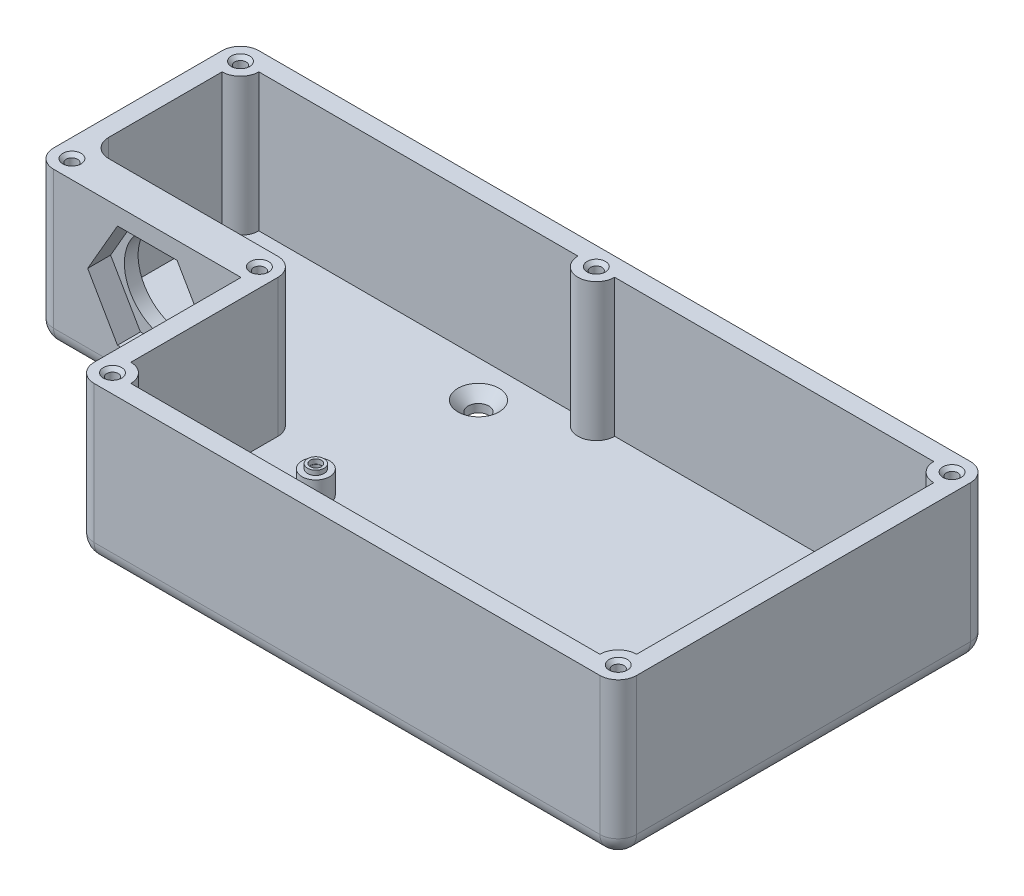
SolidWorks part; units mm, degrees
ref_plane "Alzado" through (0, 0, 0) normal (0, 0, 1) x (1, 0, 0)
ref_plane "Planta" through (0, 0, 0) normal (0, 1, 0) x (1, 0, 0)
ref_plane "Vista lateral" through (0, 0, 0) normal (1, 0, 0) x (0, 0, -1)
sketch "Croquis2" plane through (0, 0, 0) normal (0, 1, 0) x (1, 0, 0)
  line L0 (0, 0) -> (90.17, 0)
  line L1 (90.17, 0) -> (90.3175, 47.7203)
  line L2 (90.3175, 47.7203) -> (0.1588, 47.6975)
  line L3 (0.1588, 47.6975) -> (0, 0)
  circle A0 centre (5.2388, 19.05) radius 2
  circle A1 centre (85.2488, 8.7503) radius 1.5
  circle A2 centre (85.2488, 44.1516) radius 1.5
sketch "Croquis3" plane through (0, 0, 0) normal (0, 1, 0) x (1, 0, 0)
  circle A0 centre (85.2488, 8.7503) radius 1.5 construction
  circle A1 centre (85.2488, 44.1516) radius 1.5 construction
  circle A2 centre (5.2388, 19.05) radius 2 construction
  circle A3 centre (85.2488, 8.7503) radius 1.5 construction
  circle A4 centre (85.2488, 44.1516) radius 1.5 construction
  circle A5 centre (5.2388, 19.05) radius 2 construction
  circle A6 centre (5.2388, 19.05) radius 3
  circle A7 centre (85.2488, 44.1516) radius 2.5
  circle A8 centre (85.2488, 8.7503) radius 2.5
  dimension "D1" = 1
extrude "Saliente-Extruir1" add sketch "Croquis3" along normal blind 5
hole_wizard "Taladro de margen para M21" positions "Croquis6" profile "Croquis8" hole size "M2" standard "Ansi Metric" end condition through all
sketch "Croquis6" plane through (0, 5, 0) normal (0, 1, 0) x (1, 0, 0)
  point P0 (5.2388, 19.05)
  point P3 (85.2488, 44.1516)
  point P6 (85.2488, 8.7503)
sketch "Croquis8" plane through (5.2388, 5, -19.05) normal (1, 0, 0) x (0, 0, 1)
  line L0 (0, 0) -> (0, 5)
  line L1 (0, 5) -> (1.2, 5)
  line L2 (1.2, 5) -> (1.2, 0.025)
  line L3 (1.2, 0.025) -> (1.225, 0)
  line L5 (1.225, 0) -> (0, 0)
  line L6 (-1.2, 0.025) -> (-1.225, 0) construction
  line L11 (0, -6.35) -> (0, 107.95) construction
  dimension "Diámetro de taladro hasta el siguiente" = 2.4
  dimension "Profundidad de taladro hasta el siguiente" = 5
  dimension "Diámetro de avellanado cercano" = 2.45
  dimension "Ángulo de avellanado cercano" = 90
sketch "Croquis9" plane through (0, 5, 0) normal (0, 1, 0) x (1, 0, 0)
  circle A1 centre (5.2388, 19.05) radius 1.225 construction
  circle A2 centre (5.2388, 19.05) radius 1.8
  circle A3 centre (5.2388, 19.05) radius 1.225
extrude "Saliente-Extruir3" add sketch "Croquis9" along normal blind 1
sketch "Croquis10" plane through (0, 0, 0) normal (0, 1, 0) x (1, 0, 0)
  line L1 (-10, -10) -> (100.17, -10)
  line L2 (-54.8412, 30) -> (-54.8412, 62.7203)
  line L3 (-54.8412, 62.7203) -> (100.17, 62.7203)
  line L4 (100.17, -10) -> (100.17, 62.7203)
  line L5 (0, 0) -> (90.17, 0) construction
  line L8 (-54.8412, 30) -> (-10, 30)
  line L9 (-10, 30) -> (-10, -10)
  dimension "D1" = 10
  dimension "D2" = 10
  dimension "D3" = 15
  dimension "D4" = 55
  dimension "D5" = 10
  dimension "D6" = 40
extrude "Saliente-Extruir4" add sketch "Croquis10" against normal blind 4
sketch "Croquis11" plane through (0, 0, 0) normal (0, 1, 0) x (1, 0, 0)
  line L0 (104.17, -14) -> (104.17, 66.7203)
  line L1 (104.17, 66.7203) -> (-58.8412, 66.7203)
  line L2 (-58.8412, 66.7203) -> (-58.8412, 26)
  line L4 (-14, 22) -> (-14, -14)
  line L5 (-14, -14) -> (104.17, -14)
  line L6 (100.17, -10) -> (100.17, 62.7203)
  line L7 (100.17, 62.7203) -> (-54.8412, 62.7203)
  line L8 (-54.8412, 62.7203) -> (-54.8412, 30)
  line L9 (-54.8412, 30) -> (-10, 30)
  line L10 (-10, 30) -> (-10, -10)
  line L11 (-10, -10) -> (100.17, -10)
  line L12 (100.17, -10) -> (100.17, 62.7203)
  line L13 (100.17, 62.7203) -> (-54.8412, 62.7203)
  line L14 (-54.8412, 62.7203) -> (-54.8412, 30)
  line L15 (-54.8412, 30) -> (-10, 30)
  line L16 (-10, 30) -> (-10, -10)
  line L17 (-10, -10) -> (100.17, -10)
  line L18 (-58.8412, 26) -> (-58.8412, 22)
  line L19 (-58.8412, 22) -> (-14, 22)
  line L20 (-14, 26) -> (-14, -14) construction
  line L24 (-58.8412, 26) -> (-14, 26) construction
  dimension "D3" = 8
  dimension "D1" = 0
  dimension "D2" = 4
extrude "Saliente-Extruir5" add sketch "Croquis11" along normal blind 30 and the other way blind 4
sketch "Croquis12" plane through (0, 0, -22) normal (0, 0, 1) x (1, 0, 0)
  line L0 (-14, 0) -> (-14, 30) construction
  line L1 (-54.8412, 30) -> (-14, 0) construction
  line L3 (-54.8412, 30) -> (-14, 30) construction
  line L4 (-10, 0) -> (-10, 30)
  line L5 (-54.8412, 0) -> (-10, 0)
  line L6 (-54.8412, 30) -> (-54.8412, 0)
  line L7 (-10, 30) -> (-54.8412, 30)
  line L9 (-54.8412, 0) -> (-14, 0) construction
  line L14 (-21.4302, 15) -> (-27.9254, 26.25)
  line L15 (-27.9254, 26.25) -> (-40.9158, 26.25)
  line L20 (-40.9158, 26.25) -> (-47.411, 15)
  line L21 (-47.411, 15) -> (-40.9158, 3.75)
  line L22 (-40.9158, 3.75) -> (-27.9254, 3.75)
  line L23 (-27.9254, 3.75) -> (-21.4302, 15)
  line L26 (-58.8412, -4) -> (-14, -4) construction
  line L27 (-58.8412, 30) -> (-14, 30) construction
  line L28 (-14, -4) -> (-14, 30) construction
  line L31 (-54.8412, 30) -> (-54.8412, 0) construction
  circle A0 centre (-34.4206, 15) radius 11.25 construction
  dimension "D4" = 22.5
  dimension "D1" = 0
extrude "Cortar-Extruir2" cut sketch "Croquis12" against normal blind 5
sketch "Croquis13" plane through (0, 0, -27) normal (0, 0, 1) x (1, 0, 0)
  line L0 (-54.8412, 30) -> (-14, 0) construction
  circle A0 centre (-34.4206, 15) radius 10
  dimension "D1" = 20
extrude "Cortar-Extruir3" cut sketch "Croquis13" against normal blind 5
fillet "Redondeo1" radius 4 17 edges at (104.17, -4, -26.3602) (22.6644, -4, -66.7203) (-58.8412, -4, -44.3601) (-36.4206, -4, -22) (-14, -4, -4) (45.085, -4, 14) (-10, 15, -30) (-54.8412, 15, -30) (-54.8412, 15, -62.7203) (100.17, 15, -62.7203) (100.17, 15, 10) (-10, 15, 10) (-58.8412, 13, -66.7203) (104.17, 13, -66.7203) (104.17, 13, 14) (-14, 13, 14) (-58.8412, 13, -22)
sketch "Croquis15" plane through (0, 0, 0) normal (0, 1, 0) x (1, 0, 0)
  line L0 (96.17, 62.7203) -> (-50.8412, 62.7203) construction
  line L1 (-54.8412, 62.7203) -> (22.6644, 62.7203) construction
  line L2 (22.6644, 62.7203) -> (100.17, 62.7203) construction
  circle A12 centre (-54.8412, 62.7203) radius 4
  circle A13 centre (100.17, 62.7203) radius 4
  circle A14 centre (100.17, -10) radius 4
  circle A15 centre (-10, -10) radius 4
  circle A16 centre (-14, 26) radius 4
  circle A17 centre (-54.8412, 26) radius 4
  circle A18 centre (22.6644, 62.7203) radius 4
  dimension "D1" = 8
extrude "Saliente-Extruir9" add sketch "Croquis15" along normal up to surface (30 mm away) up to face at (12.9533, 30, -25.4593)
hole_wizard "Refrentado para tornillo tapón con cabeza plana de clavija de M31" positions "Croquis20" profile "Croquis19" countersink size "M3" standard "Ansi Metric"
sketch "Croquis20" plane through (0, 30, 0) normal (0, 1, 0) x (1, 0, 0)
  point P0 (-54.8412, 62.7203)
  point P3 (-54.8412, 26)
  point P6 (-14, 26)
  point P9 (-10, -10)
  point P12 (100.17, -10)
  point P15 (100.17, 62.7203)
  point P18 (22.6644, 62.7203)
sketch "Croquis19" plane through (-54.8412, 30, -62.7203) normal (1, 0, 0) x (0, 0, 1)
  line L0 (0, 0) -> (0, 10.7511)
  line L1 (0, 10.7511) -> (1.25, 10)
  line L2 (1.25, 10) -> (1.25, 0.75)
  line L3 (1.25, 0.75) -> (2, 0)
  line L5 (2, 0) -> (0, 0)
  line L6 (-1.25, 0.75) -> (-2, 0) construction
  line L10 (0, 10.7511) -> (-1.25, 10) construction
  line L11 (0, -6.35) -> (0, 107.95) construction
  dimension "Diámetro de taladro" = 2.5
  dimension "Profundidad de taladro" = 10
  dimension "Ángulo de avellanado cercano" = 4
  dimension "Ángulo de avellanado lejano" = 90
  dimension "Ángulo de perforador" = 118
sketch "Croquis25" plane through (0, 0, 0) normal (0, 1, 0) x (1, 0, 0)
  line L0 (-54.8412, 54.7203) -> (100.17, 54.7203) construction
  line L1 (-54.8412, 58.7203) -> (-54.8412, 34) construction
  line L2 (100.17, -6) -> (100.17, 58.7203) construction
  line L3 (5, 62.7203) -> (5, -10) construction
  line L4 (18.6644, 62.7203) -> (-50.8412, 62.7203) construction
  line L5 (-6, -10) -> (96.17, -10) construction
  line L6 (-10, -2) -> (100.17, -2) construction
  line L7 (-10, 26) -> (-10, -6) construction
  line L8 (100.17, -6) -> (100.17, 58.7203) construction
  line L9 (-6, -10) -> (96.17, -10) construction
  line L10 (85.17, 62.7203) -> (85.17, -10) construction
  line L11 (96.17, 62.7203) -> (26.6644, 62.7203) construction
  dimension "D1" = 8
  dimension "D2" = 15
  dimension "D3" = 8
  dimension "D4" = 15
hole_wizard "Refrentado para tornillo tapón con cabeza plana de clavija de M41" positions "Croquis28" profile "Croquis27" countersink size "M4" standard "Ansi Metric"
sketch "Croquis28" plane through (0, 0, 0) normal (0, 1, 0) x (1, 0, 0)
  line L0 (-54.8412, 54.7203) -> (100.17, 54.7203) construction
  line L1 (5, 62.7203) -> (5, -10) construction
  line L2 (85.17, 62.7203) -> (85.17, -10) construction
  line L3 (-10, -2) -> (100.17, -2) construction
  point P0 (5, 54.7203)
  point P6 (85.17, 54.7203)
  point P10 (85.17, -2)
  point P14 (5, -2)
sketch "Croquis27" plane through (5, 0, -54.7203) normal (1, 0, 0) x (0, 0, 1)
  line L0 (0, 0) -> (0, 11.3519)
  line L1 (0, 11.3519) -> (2.25, 10)
  line L2 (2.25, 10) -> (2.25, 2.23)
  line L3 (2.25, 2.23) -> (4.48, 0)
  line L5 (4.48, 0) -> (0, 0)
  line L6 (-2.25, 2.23) -> (-4.48, 0) construction
  line L10 (0, 11.3519) -> (-2.25, 10) construction
  line L11 (0, -6.35) -> (0, 107.95) construction
  dimension "Diámetro de taladro" = 4.5
  dimension "Profundidad de taladro" = 10
  dimension "Ángulo de avellanado cercano" = 8.96
  dimension "Ángulo de avellanado lejano" = 90
  dimension "Ángulo de perforador" = 118
